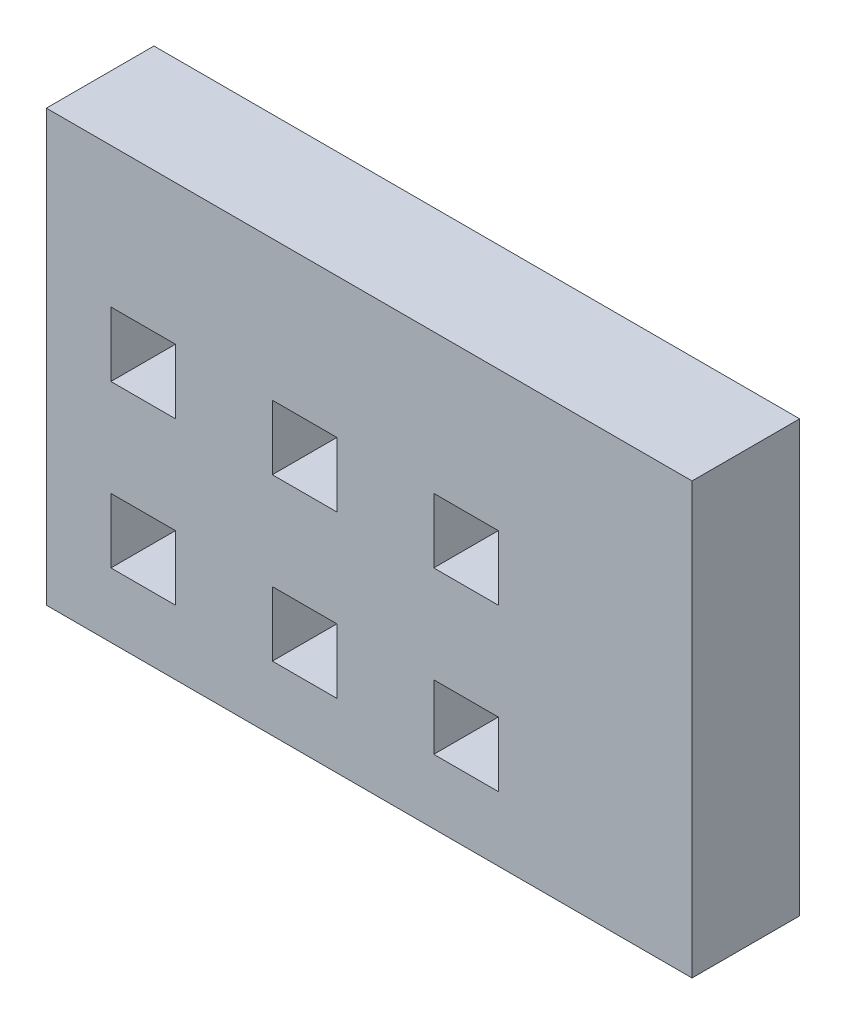
SolidWorks part; units mm, degrees
ref_plane "Front Plane" through (0, 0, 0) normal (0, 0, 1) x (1, 0, 0)
ref_plane "Top Plane" through (0, 0, 0) normal (0, 1, 0) x (1, 0, 0)
ref_plane "Right Plane" through (0, 0, 0) normal (1, 0, 0) x (0, 0, -1)
sketch "Sketch1" plane through (0, 0, 0) normal (0, 0, 1) x (1, 0, 0)
  line L1 (0, 0) -> (60, 0)
  line L2 (0, 0) -> (0, 40)
  line L3 (0, 40) -> (60, 40)
  line L4 (60, 0) -> (60, 40)
extrude "Boss-Extrude1" add sketch "Sketch1" along normal blind 10
sketch "Sketch2" plane through (0, 0, 0) normal (0, 0, 1) x (1, 0, 0)
  line L1 (6, 6) -> (12, 6)
  line L2 (6, 6) -> (6, 12)
  line L3 (6, 12) -> (12, 12)
  line L4 (12, 6) -> (12, 12)
extrude "Cut-Extrude1" cut sketch "Sketch2" along normal through all
pattern_linear "LPattern1" count 3 spacing 15 along (1, 0, 0) count 2 spacing 15 along (0, 1, 0) of "Cut-Extrude1"
